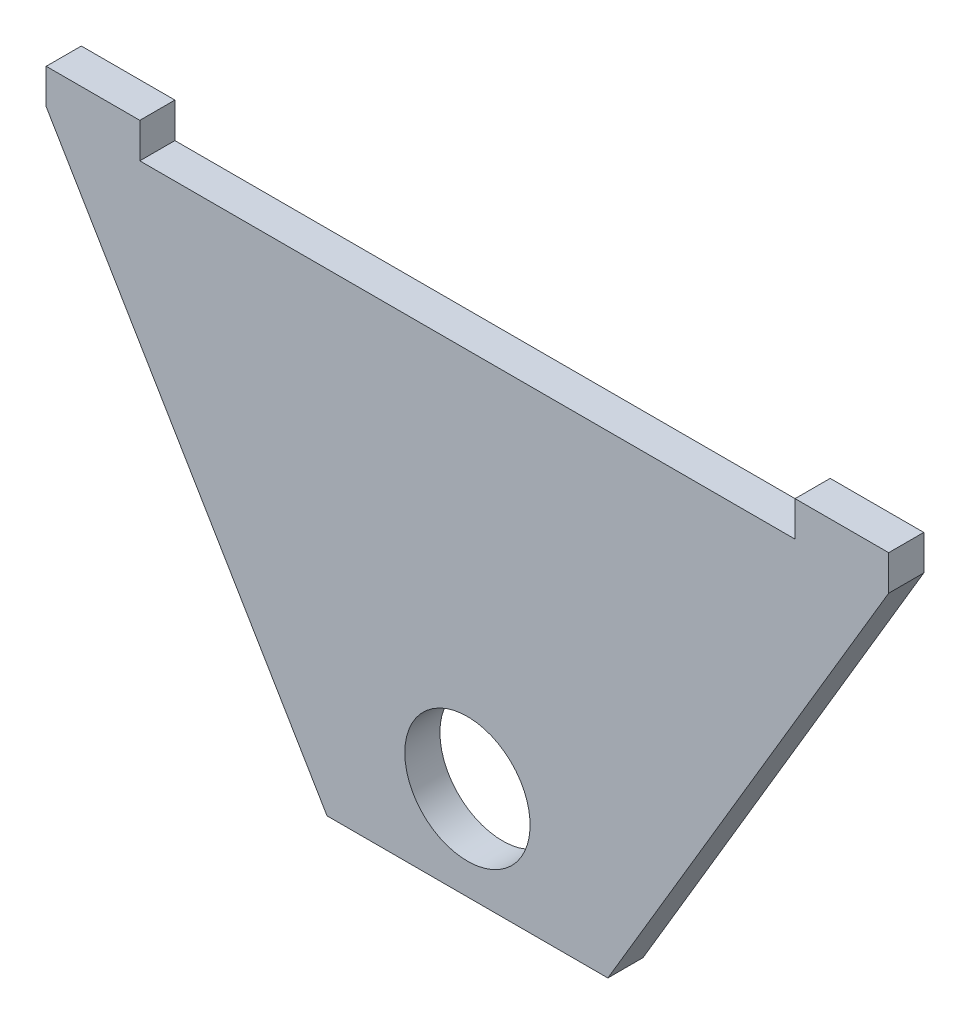
SolidWorks part; units mm, degrees
ref_plane "Front Plane" through (0, 0, 0) normal (0, 0, 1) x (1, 0, 0)
ref_plane "Top Plane" through (0, 0, 0) normal (0, 1, 0) x (1, 0, 0)
ref_plane "Right Plane" through (0, 0, 0) normal (1, 0, 0) x (0, 0, -1)
sketch "Sketch1" plane through (0, 0, 0) normal (0, 0, 1) x (1, 0, 0)
  line L1 (-38.1, 69.0245) -> (-25.4, 69.0245)
  line L2 (-25.4, 69.0245) -> (-25.4, 64.262)
  line L3 (-25.4, 64.262) -> (63.5, 64.262)
  line L4 (63.5, 64.262) -> (63.5, 69.0245)
  line L5 (63.5, 69.0245) -> (76.2, 69.0245)
  line L7 (38.1, 0) -> (0, 0)
  line L8 (19.05, 0) -> (19.05, 12.7) construction
  line L11 (-38.1, 64.262) -> (-38.1, 69.0245)
  line L14 (76.2, 64.262) -> (76.2, 69.0245)
  line L15 (0, 0) -> (-38.1, 64.262)
  line L16 (38.1, 0) -> (76.2, 64.262)
  circle A0 centre (19.05, 12.7) radius 8.5
  dimension "D1" = 17
  dimension "D2" = 12.7
  dimension "D3" = 12.7
  dimension "D4" = 114.3
  dimension "D6" = 38.1
  dimension "D7" = 4.7625
  dimension "D8" = 64.262
extrude "Boss-Extrude1" add sketch "Sketch1" along normal blind 4.7625
